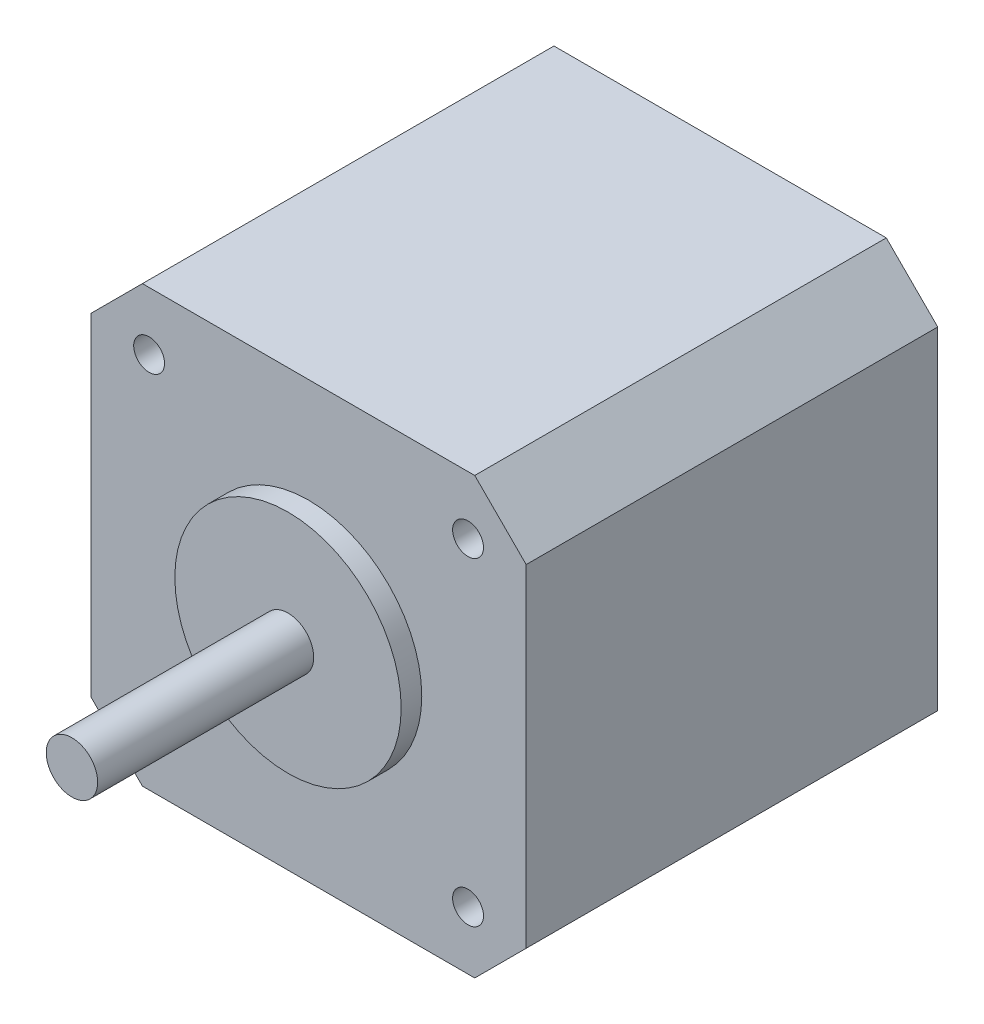
SolidWorks part; units mm, degrees
ref_plane "Alzado" through (0, 0, 0) normal (0, 0, 1) x (1, 0, 0)
ref_plane "Planta" through (0, 0, 0) normal (0, 1, 0) x (1, 0, 0)
ref_plane "Vista lateral" through (0, 0, 0) normal (1, 0, 0) x (0, 0, -1)
sketch "Croquis1" plane through (0, 0, 0) normal (0, 0, 1) x (1, 0, 0)
  line L0 (0, 21.15) -> (0, -21.15) construction
  line L1 (21.15, 21.15) -> (-21.15, 21.15)
  line L2 (21.15, 21.15) -> (21.15, -21.15)
  line L3 (21.15, -21.15) -> (-21.15, -21.15)
  line L4 (-21.15, 21.15) -> (-21.15, -21.15)
  line L5 (21.15, 21.15) -> (-21.15, -21.15) construction
  line L6 (21.15, -21.15) -> (-21.15, 21.15) construction
  line L7 (-21.15, 0) -> (21.15, 0) construction
  circle A0 centre (-15.5, 15.5) radius 1.5
  circle A1 centre (-15.5, -15.5) radius 1.5
  circle A2 centre (15.5, -15.5) radius 1.5
  circle A3 centre (15.5, 15.5) radius 1.5
  point P0 (0, 0)
  dimension "D3" = 3
  dimension "D1" = 42.3
  dimension "D2" = 42.3
  dimension "D4" = 15.5
  dimension "D5" = 15.5
extrude "Saliente-Extruir1" add sketch "Croquis1" along normal mid plane 40
sketch "Croquis2" plane through (0, 0, 20) normal (0, 0, 1) x (1, 0, 0)
  circle A0 centre (0, 0) radius 11
  dimension "D1" = 22
extrude "Saliente-Extruir2" add sketch "Croquis2" along normal blind 2
sketch "Croquis3" plane through (0, 0, 20) normal (0, 0, 1) x (1, 0, 0)
  circle A0 centre (0, 0) radius 2.5
  dimension "D1" = 5
extrude "Saliente-Extruir3" add sketch "Croquis3" along normal blind 23
chamfer "Chaflán1" distance 5 angle 45 4 edges at (-21.15, -21.15, 0) (21.15, -21.15, 0) (-21.15, 21.15, 0) (21.15, 21.15, 0)
